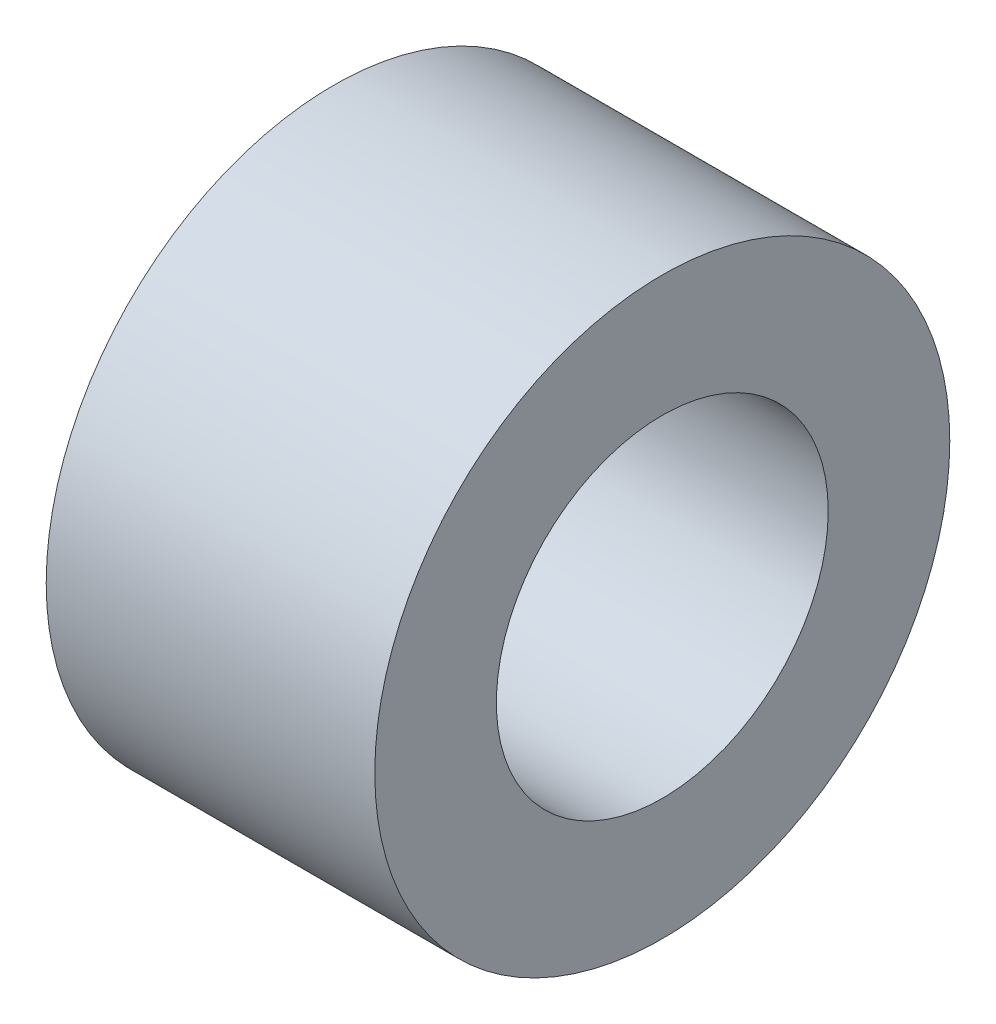
SolidWorks part; units mm, degrees
ref_plane "Front Plane" through (0, 0, 0) normal (1, 0, 0) x (0, 1, 0)
ref_plane "Top Plane" through (0, 0, 0) normal (0, 0, 1) x (0, 1, 0)
ref_plane "Right Plane" through (0, 0, 0) normal (0, 1, 0) x (-1, 0, 0)
sketch "Sketch1" plane through (0, 0, 0) normal (1, 0, 0) x (0, 1, 0)
  circle A0 centre (0, 0) radius 6.4135
  circle A1 centre (0, 0) radius 11.1125
  dimension "D1" = 12.827
  dimension "D2" = 22.225
extrude "Boss-Extrude1" add sketch "Sketch1" along normal blind 12.7
